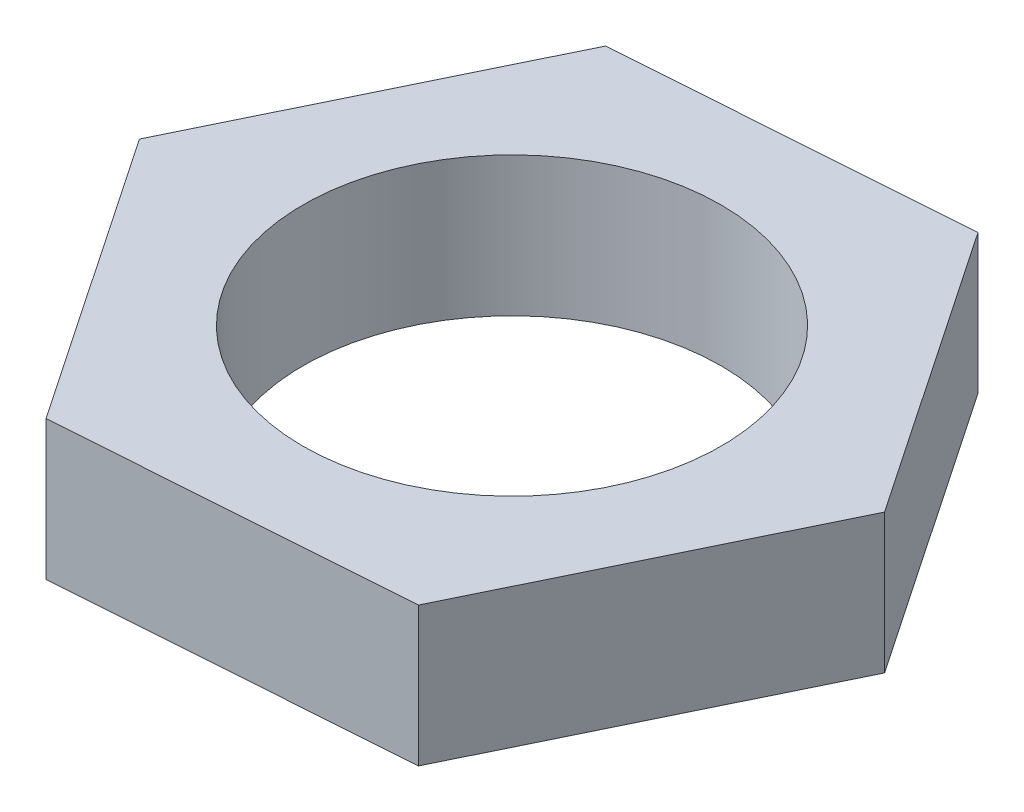
SolidWorks part; units mm, degrees
ref_plane "前视基准面" through (0, 0, 0) normal (0, 0, 1) x (1, 0, 0)
ref_plane "上视基准面" through (0, 0, 0) normal (0, 1, 0) x (1, 0, 0)
ref_plane "右视基准面" through (0, 0, 0) normal (1, 0, 0) x (0, 0, -1)
other "Configuration Table"
sketch "草图1" plane through (0, 0, 0) normal (0, 1, 0) x (1, 0, 0)
  line L1 (4.2051, -6.217) -> (7.4866, 0.5332)
  line L2 (7.4866, 0.5332) -> (3.2815, 6.7502)
  line L3 (3.2815, 6.7502) -> (-4.2051, 6.217)
  line L4 (-4.2051, 6.217) -> (-7.4866, -0.5332)
  line L5 (-7.4866, -0.5332) -> (-3.2815, -6.7502)
  line L6 (-3.2815, -6.7502) -> (4.2051, -6.217)
  circle A0 centre (0, 0) radius 6.5 construction
  circle A1 centre (0, 0) radius 4.5
  dimension "D2" = 9
  dimension "D1" = 13
extrude "凸台-拉伸1" add sketch "草图1" along normal blind 3
